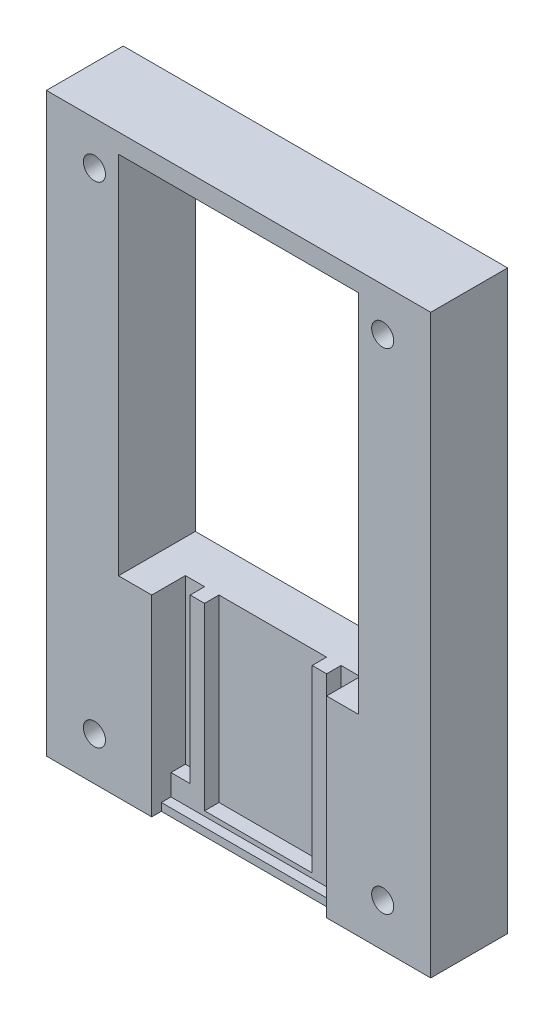
SolidWorks part; units mm, degrees
ref_plane "Front Plane" through (0, 0, 0) normal (1, 0, 0) x (0, 1, 0)
ref_plane "Top Plane" through (0, 0, 0) normal (0, 0, 1) x (0, 1, 0)
ref_plane "Right Plane" through (0, 0, 0) normal (0, 1, 0) x (-1, 0, 0)
sketch "Sketch1" plane through (0, 0, 0) normal (0, 0, 1) x (0, 1, 0)
  line L0 (0, -20) -> (60, -20) construction
  line L1 (0, 0) -> (60, 0)
  line L2 (0, 0) -> (0, -40)
  line L3 (0, -40) -> (60, -40)
  line L4 (60, 0) -> (60, -40)
  dimension "D1" = 60
  dimension "D2" = 40
extrude "Boss-Extrude1" add sketch "Sketch1" along normal blind 8
sketch "Sketch3" plane through (0, 0, 8) normal (0, 0, 1) x (1, 0, 0)
  line L0 (0, 55.5) -> (40, 55.5) construction
  line L1 (0, 60) -> (0, 0) construction
  line L2 (40, 0) -> (40, 60) construction
  line L3 (0, 4.5) -> (40, 4.5) construction
  line L4 (0, 30) -> (40, 30) construction
  line L5 (20, 60) -> (20, 0) construction
  line L6 (40, 60) -> (0, 60) construction
  line L7 (0, 0) -> (40, 0) construction
  circle A0 centre (5, 4.5) radius 1.15
  circle A1 centre (35, 4.5) radius 1.15
  circle A2 centre (5, 55.5) radius 1.15
  circle A3 centre (35, 55.5) radius 1.15
  dimension "D5" = 2.3
  dimension "D6" = 2.3
  dimension "D7" = 2.3
  dimension "D8" = 2.3
  dimension "D1" = 25.5
  dimension "D2" = 25.5
  dimension "D3" = 15
  dimension "D4" = 15
  dimension "D9" = 15
  dimension "D10" = 15
extrude "Cut-Extrude2" cut sketch "Sketch3" against normal through all
sketch "Sketch7" plane through (0, 0, 8) normal (0, 0, 1) x (1, 0, 0)
  line L0 (20, 60) -> (20, 0) construction
  line L1 (40, 60) -> (0, 60) construction
  line L2 (0, 0) -> (40, 0) construction
  line L4 (7.5, 58) -> (32.5, 58)
  line L5 (7.5, 58) -> (7.5, 20)
  line L6 (7.5, 20) -> (32.5, 20)
  line L7 (32.5, 58) -> (32.5, 20)
  point P10 (20, 20)
  dimension "D1" = 2
  dimension "D2" = 20
  dimension "D3" = 25
extrude "Cut-Extrude6" cut sketch "Sketch7" against normal through all
sketch "Sketch8" plane through (0, 0, 8) normal (0, 0, 1) x (1, 0, 0)
  line L1 (0, 0) -> (40, 0) construction
  line L4 (10.9625, 0) -> (29.1625, 0)
  line L5 (10.9625, 0) -> (10.9625, 45)
  line L6 (10.9625, 45) -> (29.1625, 45)
  line L7 (29.1625, 0) -> (29.1625, 45)
  dimension "D1" = 18.2
  dimension "D2" = 45
extrude "Cut-Extrude7" cut sketch "Sketch8" against normal blind 2
sketch "Sketch9" plane through (0, 0, 6) normal (0, 0, 1) x (1, 0, 0)
  line L1 (10.9625, 20) -> (12.9625, 20)
  line L2 (10.9625, 20) -> (10.9625, 3)
  line L3 (10.9625, 3) -> (12.9625, 3)
  line L4 (12.9625, 20) -> (12.9625, 3)
  line L5 (10.9625, 0) -> (29.1625, 0) construction
  line L6 (29.1625, 20) -> (27.1625, 20)
  line L7 (29.1625, 20) -> (29.1625, 3)
  line L8 (29.1625, 3) -> (27.1625, 3)
  line L9 (27.1625, 20) -> (27.1625, 3)
  dimension "D1" = 2
  dimension "D2" = 2
  dimension "D3" = 3
  dimension "D4" = 3
extrude "Cut-Extrude8" cut sketch "Sketch9" against normal blind 1.5
sketch "Sketch10" plane through (0, 0, 6) normal (0, 0, 1) x (1, 0, 0)
  line L0 (29.1625, 0) -> (29.1625, 20) construction
  line L1 (10.9625, 0) -> (29.1625, 0)
  line L2 (10.9625, 0) -> (10.9625, 0.8)
  line L3 (10.9625, 0.8) -> (29.1625, 0.8)
  line L4 (29.1625, 0) -> (29.1625, 0.8)
  dimension "D1" = 0.8
extrude "Boss-Extrude2" add sketch "Sketch10" along normal blind 1
sketch "Sketch11" plane through (0, 0, 6) normal (0, 0, 1) x (1, 0, 0)
  line L0 (20.0625, 20) -> (20.0625, 0) construction
  line L1 (12.9625, 20) -> (27.1625, 20) construction
  line L2 (10.9625, 0) -> (29.1625, 0) construction
  line L3 (25.6625, 1.3) -> (25.6625, 20)
  line L4 (25.6625, 1.3) -> (14.4625, 1.3)
  line L5 (25.6625, 20) -> (14.4625, 20)
  line L6 (14.4625, 1.3) -> (14.4625, 20)
  line L7 (25.6625, 1.3) -> (14.4625, 20) construction
  line L8 (25.6625, 20) -> (14.4625, 1.3) construction
  line L9 (12.9625, 3) -> (12.9625, 20) construction
  line L10 (27.1625, 20) -> (27.1625, 3) construction
  line L11 (29.1625, 0.8) -> (10.9625, 0.8) construction
  point P7 (20.0625, 10.65)
  dimension "D1" = 1.5
  dimension "D2" = 1.5
  dimension "D3" = 0.5
extrude "Cut-Extrude9" cut sketch "Sketch11" against normal blind 1.5
